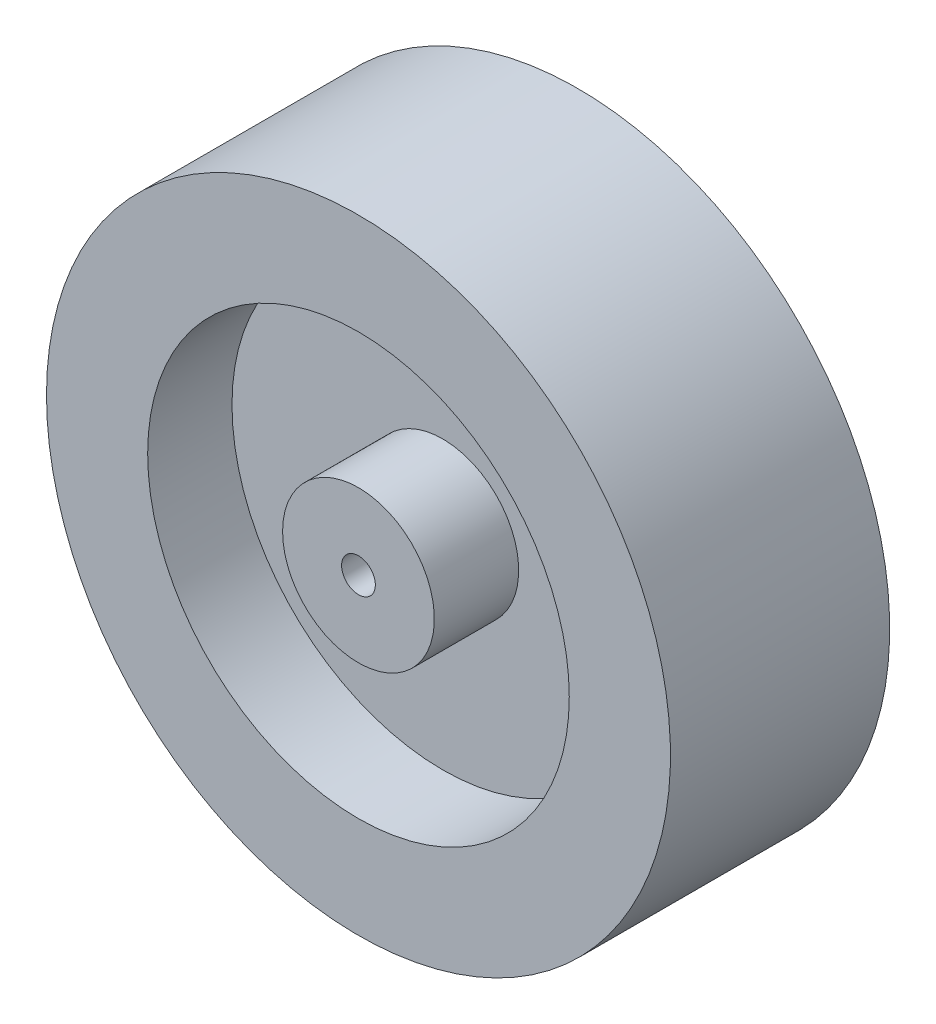
SolidWorks part; units mm, degrees
ref_plane "Front Plane" through (0, 0, 0) normal (0, 0, 1) x (1, 0, 0)
ref_plane "Top Plane" through (0, 0, 0) normal (0, 1, 0) x (1, 0, 0)
ref_plane "Right Plane" through (0, 0, 0) normal (1, 0, 0) x (0, 0, -1)
sketch "Sketch1" plane through (0, 0, 0) normal (0, 0, 1) x (1, 0, 0)
  circle A0 centre (0, 0) radius 37
  circle A1 centre (0, 0) radius 2
  dimension "D1" = 4
  dimension "D2" = 74
extrude "Boss-Extrude1" add sketch "Sketch1" along normal blind 26
sketch "Sketch2" plane through (0, 0, 0) normal (0, 0, -1) x (-1, 0, 0)
  circle A0 centre (0, 0) radius 9
  circle A1 centre (0, 0) radius 25
  circle A3 centre (0, 0) radius 37 construction
  dimension "D1" = 12
  dimension "D2" = 18
extrude "Cut-Extrude1" cut sketch "Sketch2" against normal blind 10
ref_plane "Plane1" through (0, 0, 13) normal (0, 0, -1) x (-1, 0, 0)
mirror "Mirror1" about plane through (0, 0, 13) normal (0, 0, -1) of "Cut-Extrude1"
